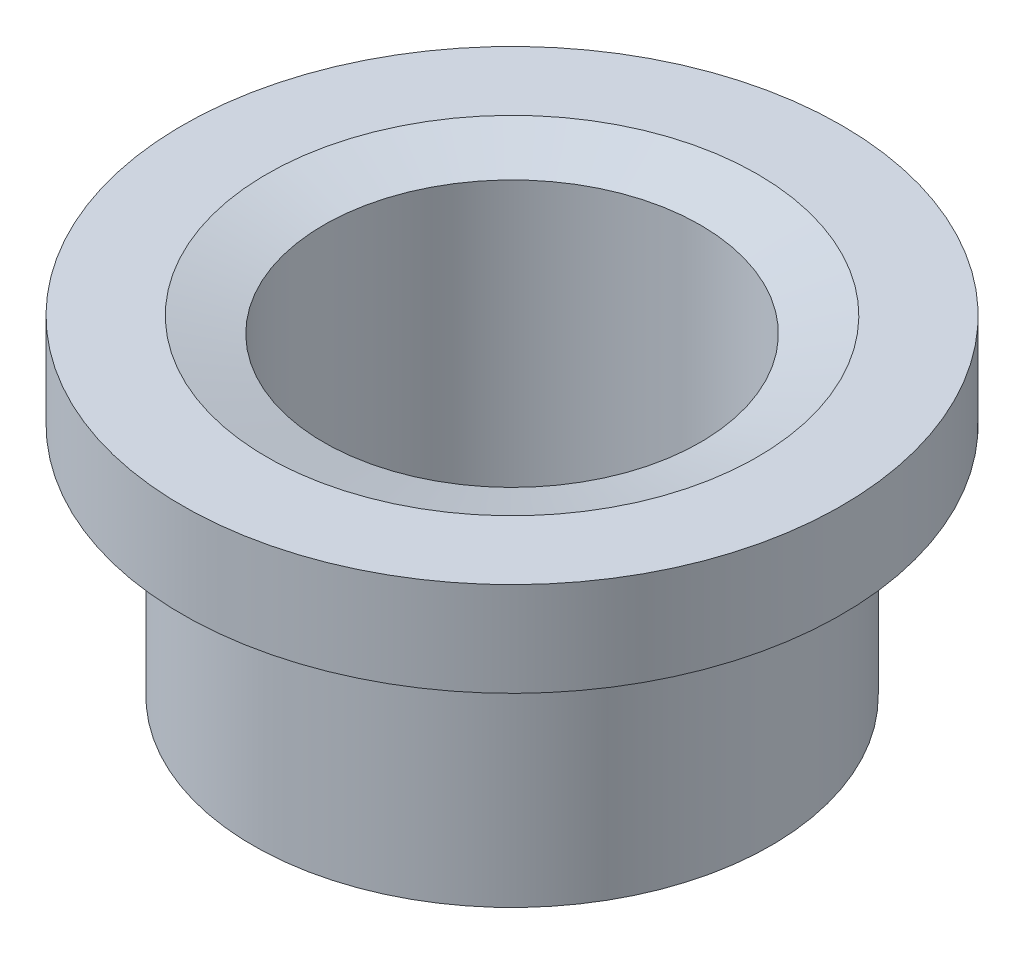
SolidWorks part; units mm, degrees
ref_plane "前视基准面" through (0, 0, 0) normal (0, 0, 1) x (1, 0, 0)
ref_plane "上视基准面" through (0, 0, 0) normal (0, 1, 0) x (1, 0, 0)
ref_plane "右视基准面" through (0, 0, 0) normal (1, 0, 0) x (0, 0, -1)
other "Configuration Table"
sketch "草图1" plane through (0, 0, 0) normal (0, 0, 1) x (1, 0, 0)
  line L0 (12, 0) -> (16.5, 0)
  line L1 (16.5, 0) -> (16.5, 15)
  line L2 (16.5, 15) -> (21, 15)
  line L3 (21, 15) -> (21, 21)
  line L4 (21, 21) -> (15.625, 21)
  line L5 (15.625, 21) -> (15.625, 20) construction
  line L6 (12, 20) -> (15.625, 20) construction
  line L7 (12, 20) -> (12, 0)
  line L8 (0, 0) -> (0, 16.7241) construction
  line L9 (15.625, 21) -> (12, 20)
  dimension "D1" = 12
  dimension "D2" = 16.5
  dimension "D3" = 6
  dimension "D4" = 15
  dimension "D5" = 15.625
  dimension "D6" = 21
  dimension "D7" = 1
revolve "旋转1" add sketch "草图1" angle 360 about L8
